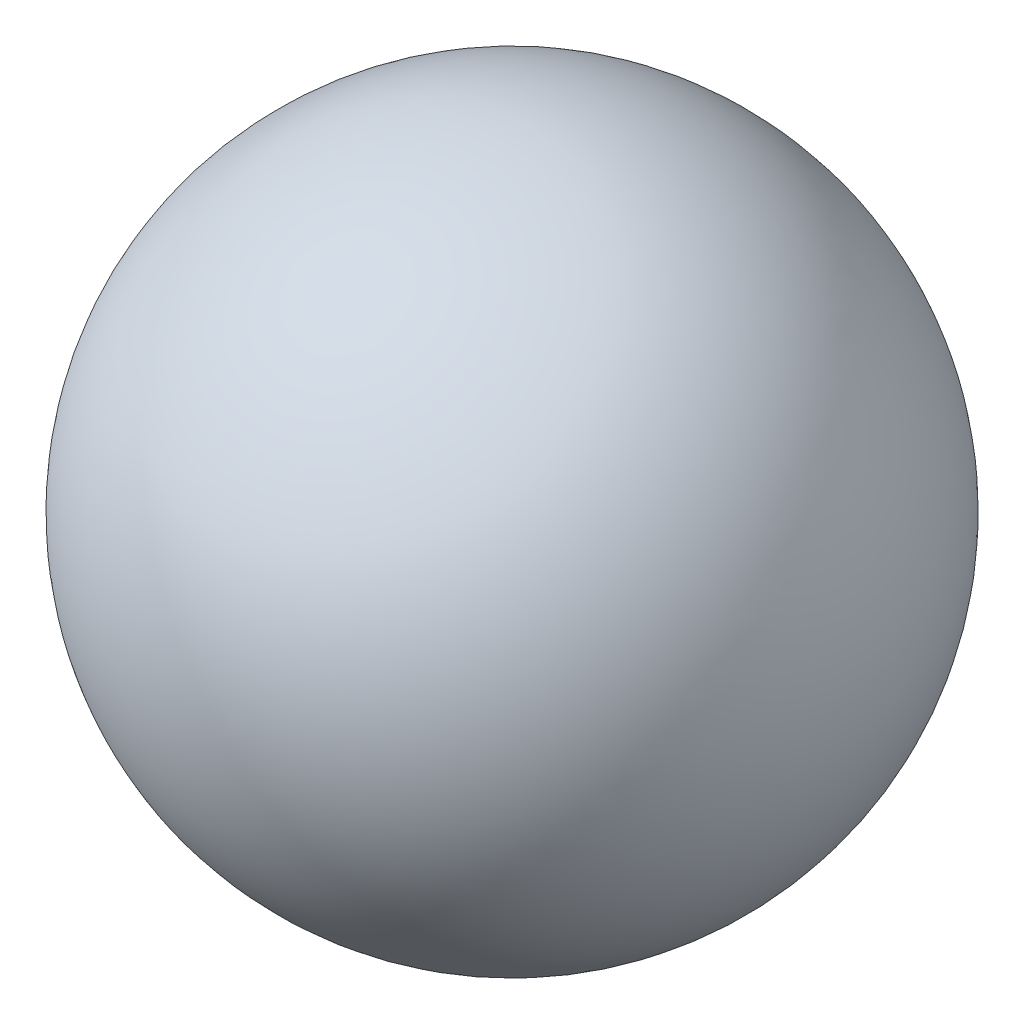
SolidWorks part; units mm, degrees
ref_plane "Front Plane" through (0, 0, 0) normal (1, 0, 0) x (0, 1, 0)
ref_plane "Top Plane" through (0, 0, 0) normal (0, 0, 1) x (0, 1, 0)
ref_plane "Right Plane" through (0, 0, 0) normal (0, 1, 0) x (-1, 0, 0)
sketch "Sketch1" plane through (0, 0, 0) normal (0, 1, 0) x (-1, 0, 0)
  line L0 (0, 28.5) -> (0, -28.5)
  arc A0 (0, 28.5) -> (0, -28.5) centre (0, 0) ccw
  point P6 (0, 0)
  dimension "D1" = 57
  dimension "D2" = 57
revolve "Revolve1" add sketch "Sketch1" angle 360 about L0
